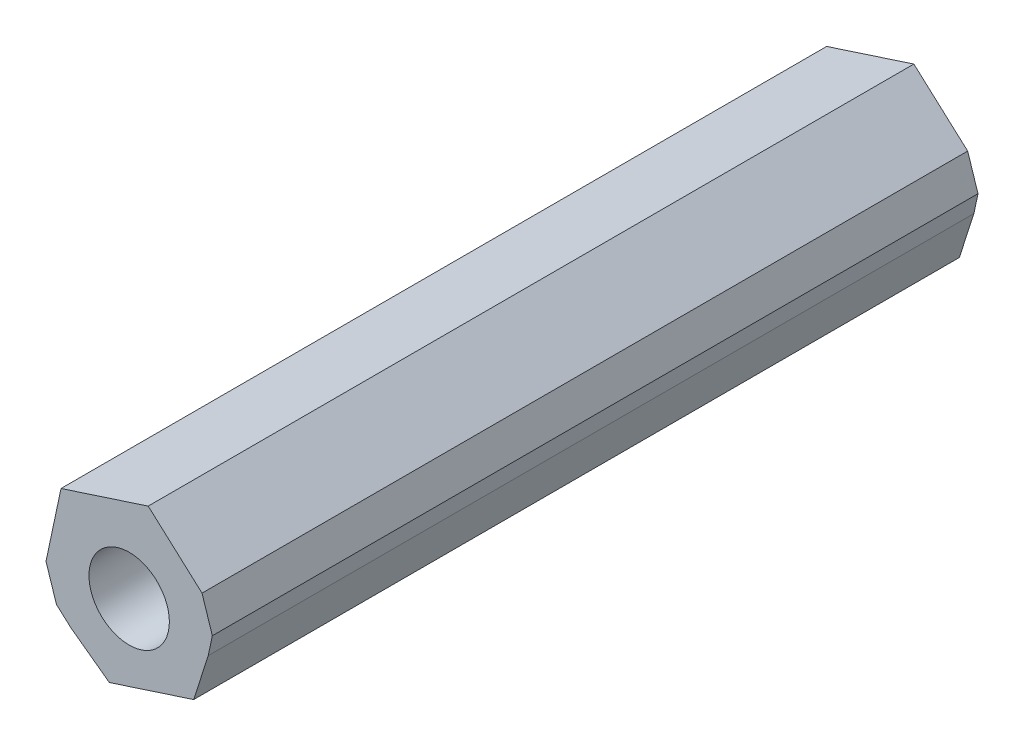
SolidWorks part; units mm, degrees
ref_plane "前视基准面" through (0, 0, 0) normal (0, 0, 1) x (1, 0, 0)
ref_plane "上视基准面" through (0, 0, 0) normal (0, 1, 0) x (1, 0, 0)
ref_plane "右视基准面" through (0, 0, 0) normal (1, 0, 0) x (0, 0, -1)
sketch "草图2" plane through (0, 0, 0) normal (0, 0, 1) x (1, 0, 0)
  line L0 (-0.6157, -2.5658) -> (2.0063, -1.7139)
  line L3 (0.5926, 2.7877) -> (-2.1179, 1.9071)
  line L8 (2.5859, 0.2945) -> (2.4587, -0.3039)
  line L9 (-2.1179, 1.9071) -> (-2.5846, -0.2884)
  line L10 (-2.2605, -1.2858) -> (-1.8106, -1.691)
  line L12 (2.7105, 0.8807) -> (-2.7105, -0.8807) construction
  line L13 (2.2652, 1.2816) -> (2.5859, 0.2945)
  line L14 (-2.5846, -0.2884) -> (-2.2605, -1.2858)
  line L15 (2.4587, -0.3039) -> (2.0063, -1.7139)
  line L16 (0.5926, 2.7877) -> (2.2652, 1.2816)
  line L17 (-1.8106, -1.691) -> (-0.6157, -2.5658)
  circle A1 centre (0, 0) radius 1.25
  dimension "D1" = 2.25
extrude "凸台-拉伸1" add sketch "草图2" along normal blind 23.8
